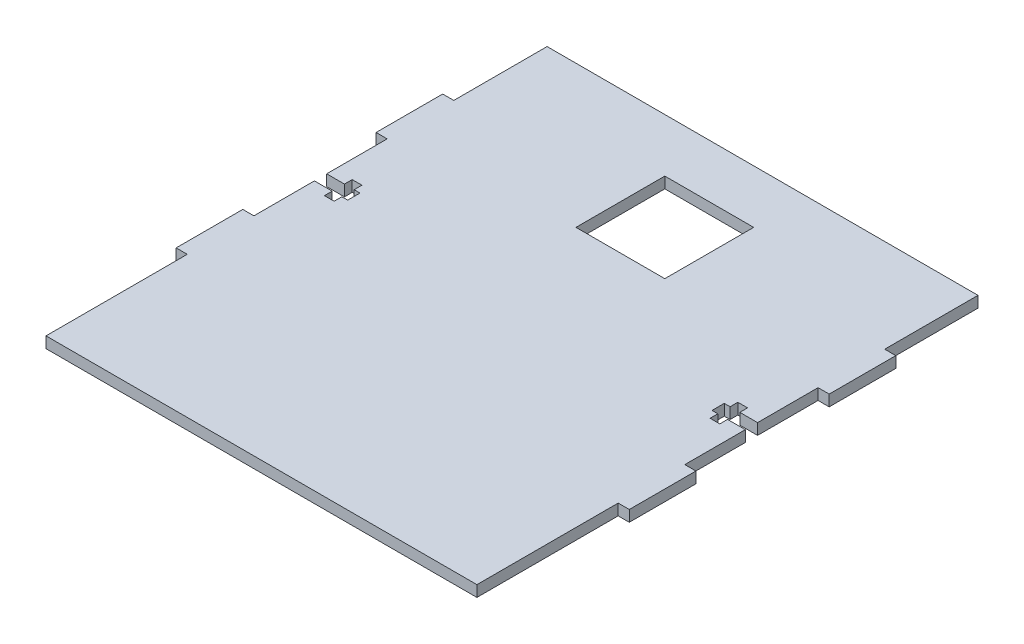
SolidWorks part; units mm, degrees
ref_plane "Front Plane" through (0, 0, 0) normal (0, 0, 1) x (1, 0, 0)
ref_plane "Top Plane" through (0, 0, 0) normal (0, 1, 0) x (1, 0, 0)
ref_plane "Right Plane" through (0, 0, 0) normal (1, 0, 0) x (0, 0, -1)
sketch "Sketch1" plane through (0, 0, 0) normal (0, 1, 0) x (1, 0, 0)
  line L0 (123.19, 116.586) -> (123.19, 143.256)
  line L1 (0, 0) -> (123.19, 0)
  line L2 (0, 0) -> (0, 40.386)
  line L3 (0, 143.256) -> (123.19, 143.256)
  line L4 (123.19, 0) -> (123.19, 40.386)
  line L5 (48.895, 128.016) -> (74.295, 128.016)
  line L6 (48.895, 128.016) -> (48.895, 102.616)
  line L7 (48.895, 102.616) -> (74.295, 102.616)
  line L8 (74.295, 128.016) -> (74.295, 102.616)
  line L9 (123.19, 116.586) -> (126.365, 116.586)
  line L10 (123.19, 59.436) -> (123.19, 76.7334)
  line L11 (123.19, 97.536) -> (126.365, 97.536)
  line L12 (126.365, 116.586) -> (126.365, 97.536)
  line L13 (0, 116.586) -> (-3.175, 116.586)
  line L14 (115.3319, 76.7334) -> (115.3319, 74.5173)
  line L15 (0, 97.536) -> (-3.175, 97.536)
  line L16 (-3.175, 116.586) -> (-3.175, 97.536)
  line L17 (123.19, 40.386) -> (126.365, 40.386)
  line L19 (123.19, 59.436) -> (126.365, 59.436)
  line L20 (126.365, 40.386) -> (126.365, 59.436)
  line L21 (0, 59.436) -> (-3.175, 59.436)
  line L22 (0, 116.586) -> (0, 143.256)
  line L23 (0, 40.386) -> (-3.175, 40.386)
  line L24 (-3.175, 59.436) -> (-3.175, 40.386)
  line L26 (123.19, 80.2386) -> (123.19, 76.7334) construction
  line L29 (118.11, 80.2386) -> (123.19, 80.2386)
  line L30 (118.11, 76.7334) -> (123.19, 76.7334)
  line L31 (123.19, 78.486) -> (113.665, 78.486) construction
  line L32 (115.3319, 82.4547) -> (118.11, 82.4547)
  line L33 (115.3319, 82.4547) -> (115.3319, 80.2386)
  line L34 (115.3319, 74.5173) -> (118.11, 74.5173)
  line L35 (118.11, 82.4547) -> (118.11, 80.2386)
  line L36 (113.665, 80.2386) -> (115.3319, 80.2386)
  line L37 (113.665, 80.2386) -> (113.665, 76.7334)
  line L38 (113.665, 76.7334) -> (115.3319, 76.7334)
  line L39 (118.11, 76.7334) -> (118.11, 74.5173)
  line L41 (123.19, 80.2386) -> (123.19, 97.536)
  line L42 (61.595, 102.616) -> (61.595, 0) construction
  line L43 (9.525, 80.2386) -> (7.8581, 80.2386)
  line L45 (0, 76.7334) -> (0, 80.2386) construction
  line L48 (5.08, 74.5172) -> (5.08, 76.7334)
  line L49 (5.08, 80.2386) -> (5.08, 82.4547)
  line L50 (5.08, 80.2386) -> (0, 80.2386)
  line L51 (0, 78.486) -> (9.525, 78.486) construction
  line L53 (7.8581, 74.5172) -> (7.8581, 76.7334)
  line L54 (7.8581, 74.5172) -> (5.08, 74.5172)
  line L56 (7.8581, 80.2386) -> (7.8581, 82.4547)
  line L57 (9.525, 76.7334) -> (7.8581, 76.7334)
  line L58 (7.8581, 82.4547) -> (5.08, 82.4547)
  line L60 (0, 76.7334) -> (0, 59.436)
  line L61 (5.08, 76.7334) -> (0, 76.7334)
  line L62 (0, 97.536) -> (0, 80.2386)
  line L63 (9.525, 76.7334) -> (9.525, 80.2386)
  point P15 (0, 0)
  point P25 (0, 0)
  dimension "D1" = 143.256
  dimension "D2" = 123.19
  dimension "D3" = 102.616
  dimension "D4" = 25.4
  dimension "D5" = 25.4
  dimension "D6" = 48.895
  dimension "D7" = 19.05
  dimension "D8" = 26.67
  dimension "D9" = 3.175
  dimension "D10" = 40.386
  dimension "D11" = 5.08
  dimension "D12" = 3.5052
  dimension "D13" = 7.9375
  dimension "D14" = 5.08
  dimension "D16" = 2.7781
  dimension "D17" = 9.525
  dimension "D18" = 64.77
  dimension "D20" = 3.5052
  dimension "D21" = 7.9375
  dimension "D23" = 2.7781
  dimension "D25" = 9.525
extrude "Boss-Extrude1" add sketch "Sketch1" along normal blind 3.175
